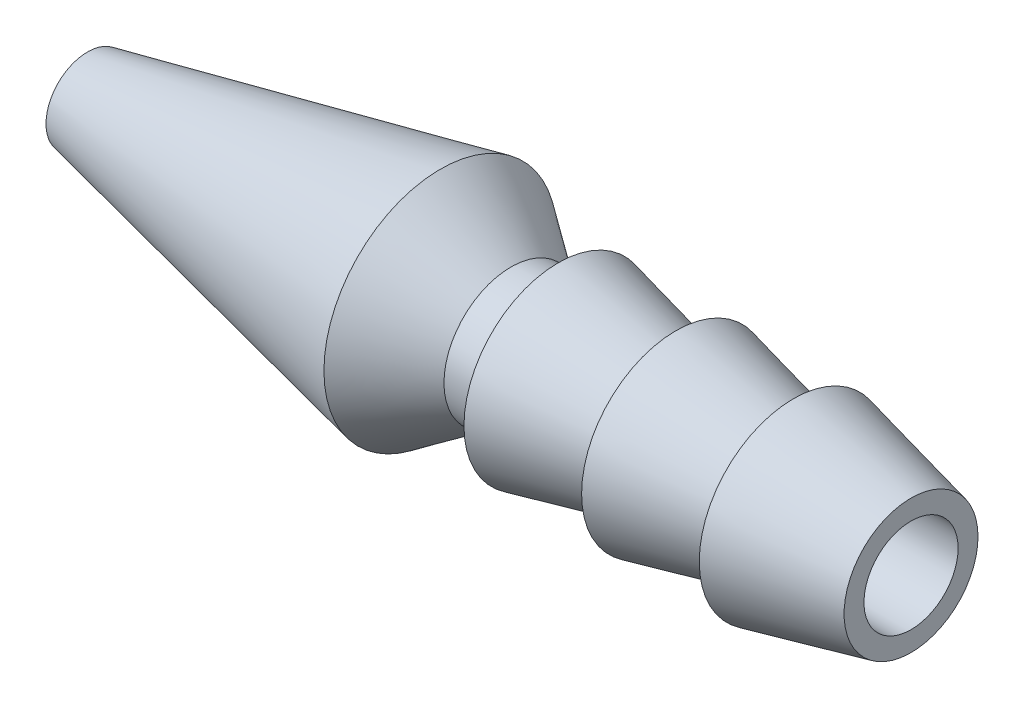
SolidWorks part; units mm, degrees
ref_plane "Front Plane" through (0, 0, 0) normal (0, 0, 1) x (1, 0, 0)
ref_plane "Top Plane" through (0, 0, 0) normal (0, 1, 0) x (1, 0, 0)
ref_plane "Right Plane" through (0, 0, 0) normal (1, 0, 0) x (0, 0, -1)
sketch "Sketch1" plane through (0, 0, 0) normal (1, 0, 0) x (0, 0, -1)
  circle A0 centre (0, 0) radius 4
extrude "Boss-Extrude1" add sketch "Sketch1" along normal blind 5 draft 13
sketch "Sketch2" plane through (5, 0, 0) normal (1, 0, 0) x (0, 0, -1)
  circle A0 centre (0, 0) radius 4
extrude "Boss-Extrude2" add sketch "Sketch2" along normal blind 5 draft 13
sketch "Sketch3" plane through (10, 0, 0) normal (1, 0, 0) x (0, 0, -1)
  circle A0 centre (0, 0) radius 4
extrude "Boss-Extrude3" add sketch "Sketch3" along normal blind 5 draft 13
sketch "Sketch4" plane through (0, 0, 0) normal (-1, 0, 0) x (0, 0, 1)
  circle A0 centre (0, 0) radius 2.85
extrude "Boss-Extrude4" add sketch "Sketch4" along normal blind 2
sketch "Sketch5" plane through (-2, 0, 0) normal (-1, 0, 0) x (0, 0, 1)
  circle A0 centre (0, 0) radius 2.85
extrude "Boss-Extrude5" add sketch "Sketch5" along normal blind 3 draft 35 draft outward yes
sketch "Sketch6" plane through (-5, 0, 0) normal (-1, 0, 0) x (0, 0, 1)
  circle A0 centre (0, 0) radius 4.9506
extrude "Boss-Extrude6" add sketch "Sketch6" along normal blind 15 draft 12
sketch "Sketch9" plane through (15, 0, 0) normal (1, 0, 0) x (0, 0, -1)
  circle A0 centre (0, 0) radius 2
extrude "Cut-Extrude1" cut sketch "Sketch9" against normal blind 20
sketch "Sketch11" plane through (-20, 0, 0) normal (-1, 0, 0) x (0, 0, 1)
  circle A0 centre (0, 0) radius 0.5
extrude "Cut-Extrude2" cut sketch "Sketch11" against normal blind 15 draft 5.8 draft outward yes
